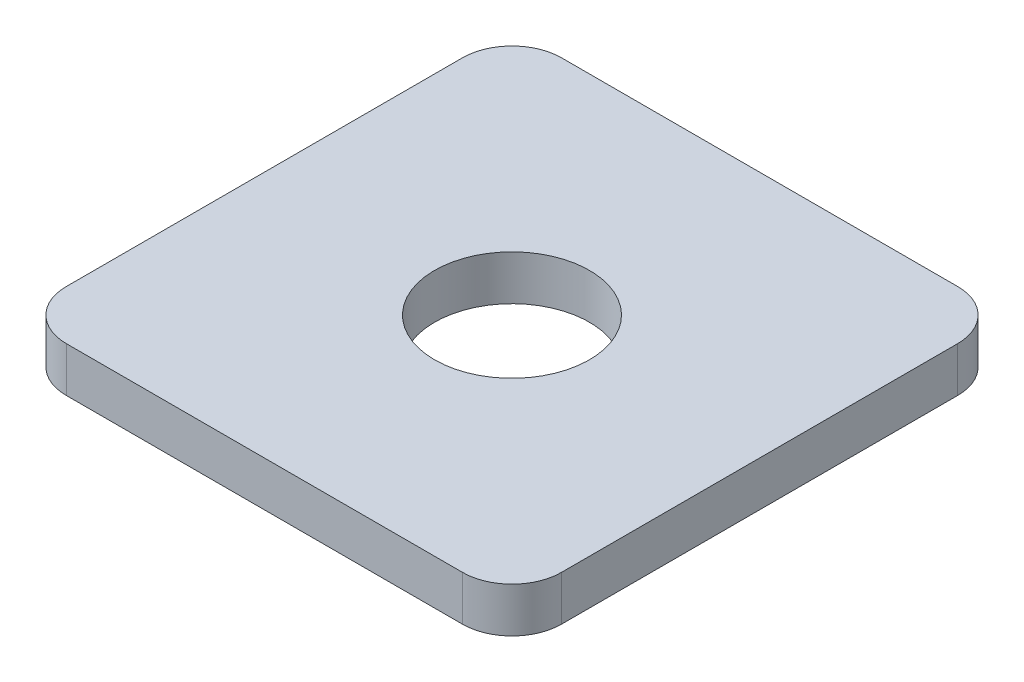
SolidWorks part; units mm, degrees
ref_plane "Front Plane" through (0, 0, 0) normal (0, 0, 1) x (1, 0, 0)
ref_plane "Top Plane" through (0, 0, 0) normal (0, 1, 0) x (1, 0, 0)
ref_plane "Right Plane" through (0, 0, 0) normal (1, 0, 0) x (0, 0, -1)
sketch "Sketch1" plane through (0, 0, 0) normal (0, 1, 0) x (1, 0, 0)
  line L1 (7, 0) -> (63, 0)
  line L2 (0, 7) -> (0, 63)
  line L3 (7, 70) -> (63, 70)
  line L4 (70, 7) -> (70, 63)
  arc A0 (63, 0) -> (70, 7) centre (63, 7) ccw
  arc A1 (7, 0) -> (0, 7) centre (7, 7) cw
  arc A2 (0, 63) -> (7, 70) centre (7, 63) cw
  arc A3 (63, 70) -> (70, 63) centre (63, 63) cw
  point P7 (70, 0)
  point P10 (0, 0)
  point P15 (70, 70)
  dimension "D3" = 7
  dimension "D1" = 70
  dimension "D2" = 70
extrude "Boss-Extrude1" add sketch "Sketch1" along normal blind 6.35
sketch "Sketch2" plane through (0, 6.35, 0) normal (0, 1, 0) x (1, 0, 0)
  line L0 (35, 70) -> (35, 0) construction
  line L1 (63, 70) -> (7, 70) construction
  line L2 (7, 0) -> (63, 0) construction
  line L3 (0, 35) -> (70, 35) construction
  line L4 (0, 63) -> (0, 7) construction
  line L5 (70, 7) -> (70, 63) construction
  circle A0 centre (35, 35) radius 10.95
  dimension "D1" = 21.9
extrude "Cut-Extrude1" cut sketch "Sketch2" against normal blind 6.35
